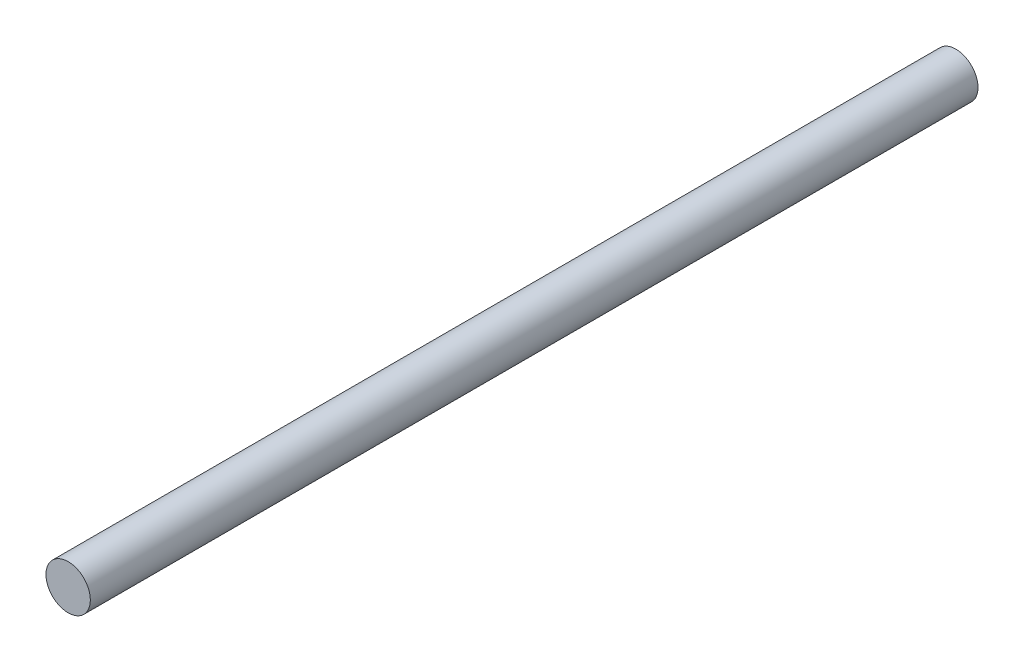
SolidWorks part; units mm, degrees
ref_plane "前视基准面" through (0, 0, 0) normal (0, 0, 1) x (1, 0, 0)
ref_plane "上视基准面" through (0, 0, 0) normal (0, 1, 0) x (1, 0, 0)
ref_plane "右视基准面" through (0, 0, 0) normal (1, 0, 0) x (0, 0, -1)
sketch "草图1" plane through (0, 0, 0) normal (0, 0, 1) x (1, 0, 0)
  circle A0 centre (0, 0) radius 10
  dimension "D1" = 20
extrude "凸台-拉伸1" add sketch "草图1" along normal blind 400
